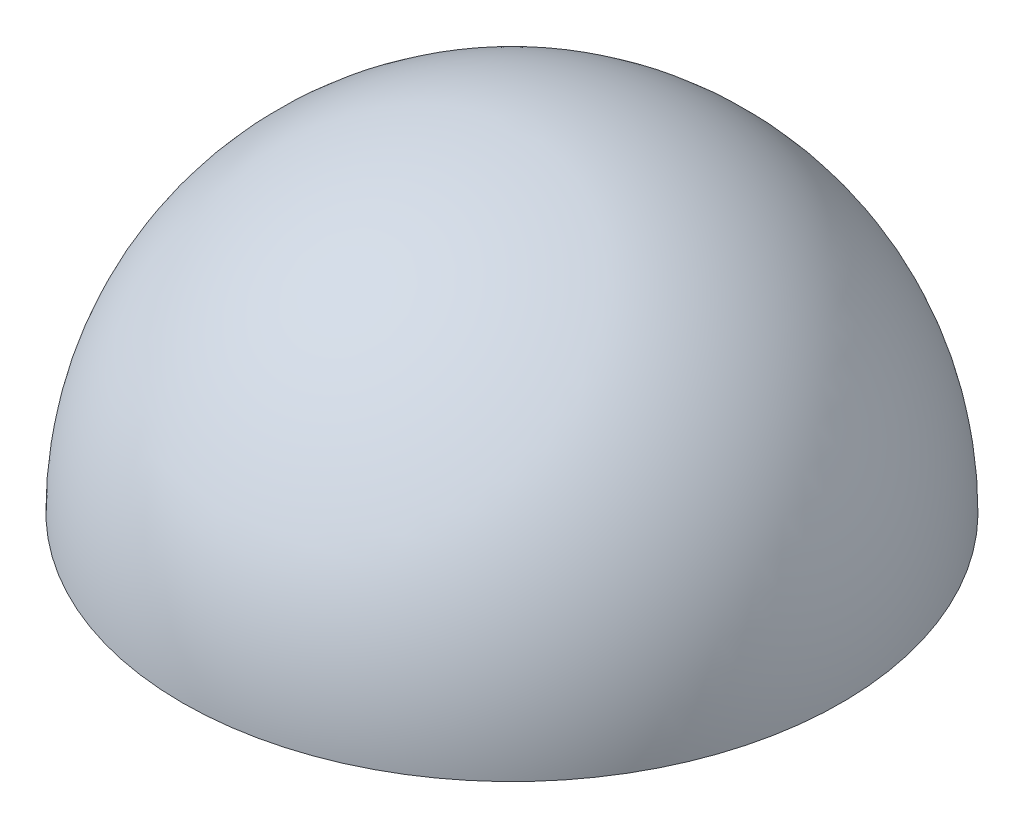
SolidWorks part; units mm, degrees
material "AISI 1020 Steel, Cold Rolled"
ref_plane "Front Plane" through (0, 0, 0) normal (0, 0, 1) x (1, 0, 0)
ref_plane "Top Plane" through (0, 0, 0) normal (0, 1, 0) x (1, 0, 0)
ref_plane "Right Plane" through (0, 0, 0) normal (1, 0, 0) x (0, 0, -1)
sketch "Sketch1" plane through (0, 0, 0) normal (0, 1, 0) x (1, 0, 0)
  line L0 (0, 0) -> (20, 0) construction
  line L1 (0, 0) -> (20, 0)
  arc A0 (0, 0) -> (20, 0) centre (10, 0) cw
  dimension "D2" = 10
  dimension "D1" = 20
revolve "Revolve1" add sketch "Sketch1" angle 180 about L0
hole_wizard "Ø6.0mm Dowel Hole1" positions "Sketch5" profile "Sketch4" hole size "Ø6.0" standard "ISO"
sketch "Sketch5" plane through (0, 0, 0) normal (0, -1, 0) x (-1, 0, 0)
  line L1 (-1000, 0) -> (49000, 0) construction
  point P0 (-10, 0)
  dimension "D1" = 10
sketch "Sketch4" plane through (10, 0, 0) normal (1, 0, 0) x (0, 0, -1)
  line L0 (0, 0) -> (0, 5.8026)
  line L1 (0, 5.8026) -> (3, 4)
  line L2 (3, 4) -> (3, 0)
  line L5 (3, 0) -> (0, 0)
  line L10 (0, 5.8026) -> (-3, 4) construction
  line L11 (0, -6.35) -> (0, 107.95) construction
  dimension "Hole Dia." = 6
  dimension "Hole Depth" = 4
  dimension "Drill Angle" = 118
